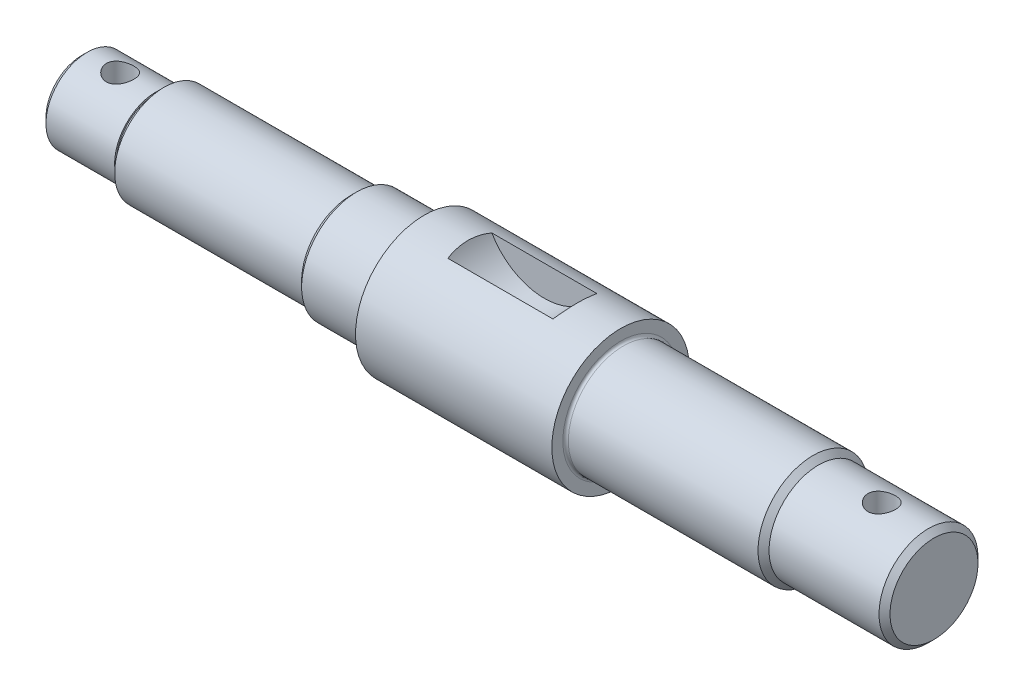
SolidWorks part; units mm, degrees
ref_plane "Front Plane" through (0, 0, 0) normal (0, 0, 1) x (1, 0, 0)
ref_plane "Top Plane" through (0, 0, 0) normal (0, 1, 0) x (1, 0, 0)
ref_plane "Right Plane" through (0, 0, 0) normal (1, 0, 0) x (0, 0, -1)
sketch "Sketch1" plane through (0, 0, 0) normal (0, 0, 1) x (1, 0, 0)
  line L0 (0, 0) -> (0, 6.5)
  line L1 (1, 7.5) -> (13.5, 7.5)
  line L2 (13.5, 7.5) -> (13.5, 7.2)
  line L3 (13.5, 7.2) -> (15, 7.2)
  line L4 (15, 7.2) -> (15, 9)
  line L5 (15, 9) -> (49, 9)
  line L6 (49, 9) -> (50, 10)
  line L7 (50, 10) -> (61.8, 10)
  line L8 (62.3, 10.5) -> (62.3, 12.5)
  line L9 (62.3, 12.5) -> (98, 12.5)
  line L10 (98, 12.5) -> (98, 10.5)
  line L11 (98.5, 10) -> (133, 10)
  line L12 (133, 10) -> (134, 9)
  line L13 (134, 9) -> (155, 9)
  line L14 (155, 9) -> (155, 0)
  line L15 (155, 0) -> (0, 0)
  line L16 (0, 6.5) -> (1, 7.5)
  arc A0 (98, 10.5) -> (98.5, 10) centre (98.5, 10.5) ccw
  arc A1 (61.8, 10) -> (62.3, 10.5) centre (61.8, 10.5) ccw
  point P1 (0, 7.5)
  point P19 (98, 10)
  dimension "D14" = 0.5
  dimension "D1" = 155
  dimension "D2" = 7.5
  dimension "D3" = 1.5
  dimension "D4" = 34
  dimension "D5" = 9
  dimension "D6" = 0.3
  dimension "D7" = 10
  dimension "D8" = 45
  dimension "D9" = 12.5
  dimension "D10" = 35.7
  dimension "D11" = 35
  dimension "D12" = 21
  dimension "D13" = 135
  dimension "D15" = 1
  dimension "D16" = 45
  dimension "D17" = 106
revolve "Revolve1" add sketch "Sketch1" angle 360 about L15
chamfer "Chamfer1" distance 1 angle 45 1 edges at (155, 0, -9)
sketch "Sketch2" plane through (0, 0, 0) normal (0, 0, 1) x (1, 0, 0)
  line L0 (80.15, -12.5) -> (80.15, 17.3) construction
  line L1 (62.3, -12.5) -> (98, -12.5) construction
  line L2 (62.3, 0) -> (98, 0) construction
  line L3 (62.3, 12.5) -> (62.3, -12.5) construction
  line L4 (98, -10.5) -> (98, 10.5) construction
  circle A0 centre (80.15, 17.3) radius 11
  dimension "D2" = 22
  dimension "D1" = 17.3
extrude "Cut-Extrude1" cut sketch "Sketch2" against normal mid plane 8
sketch "Sketch3" plane through (0, 0, 0) normal (0, 1, 0) x (1, 0, 0)
  line L3 (15, 9) -> (15, -9) construction
  line L4 (13.5, 7.5) -> (1, 7.5) construction
  line L5 (134, 9) -> (134, -9) construction
  line L6 (154, 9) -> (134, 9) construction
  circle A0 centre (7, 0) radius 2.5
  circle A1 centre (145.5, 0) radius 2.5
  dimension "D1" = 5
  dimension "D2" = 5
  dimension "D3" = 8
  dimension "D4" = 7.5
  dimension "D5" = 11.5
  dimension "D6" = 9
extrude "Cut-Extrude2" cut sketch "Sketch3" against normal through all both and the other way through all
